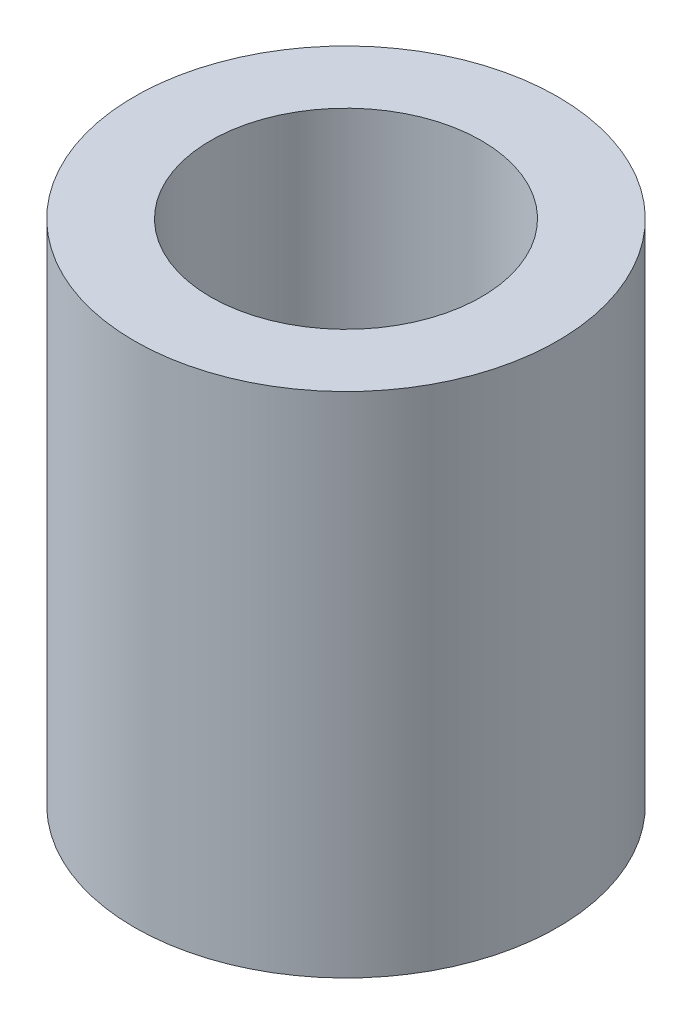
SolidWorks part; units mm, degrees
material "ABS"
ref_plane "Front Plane" through (0, 0, 0) normal (0, 0, 1) x (1, 0, 0)
ref_plane "Top Plane" through (0, 0, 0) normal (0, 1, 0) x (1, 0, 0)
ref_plane "Right Plane" through (0, 0, 0) normal (1, 0, 0) x (0, 0, -1)
sketch "Sketch1" plane through (0, 0, 0) normal (0, 1, 0) x (1, 0, 0)
  circle A0 centre (0, 0) radius 2.5
  dimension "D1" = 5
extrude "Boss-Extrude1" add sketch "Sketch1" along normal mid plane 6
hole_wizard "M3 Clearance Hole1" positions "Sketch2" profile "Sketch3" hole size "M3" standard "ANSI Metric" end condition through all
sketch "Sketch2" plane through (0, 3, 0) normal (0, 1, 0) x (1, 0, 0)
  point P0 (0, 0)
sketch "Sketch3" plane through (0, 3, 0) normal (1, 0, 0) x (0, 0, 1)
  line L0 (0, 0) -> (0, 6)
  line L1 (0, 6) -> (1.6, 6)
  line L2 (1.6, 6) -> (1.6, 0)
  line L5 (1.6, 0) -> (0, 0)
  line L11 (0, -6.35) -> (0, 107.95) construction
  dimension "Thru Hole Dia." = 3.2
  dimension "Thru Hole Depth" = 6
